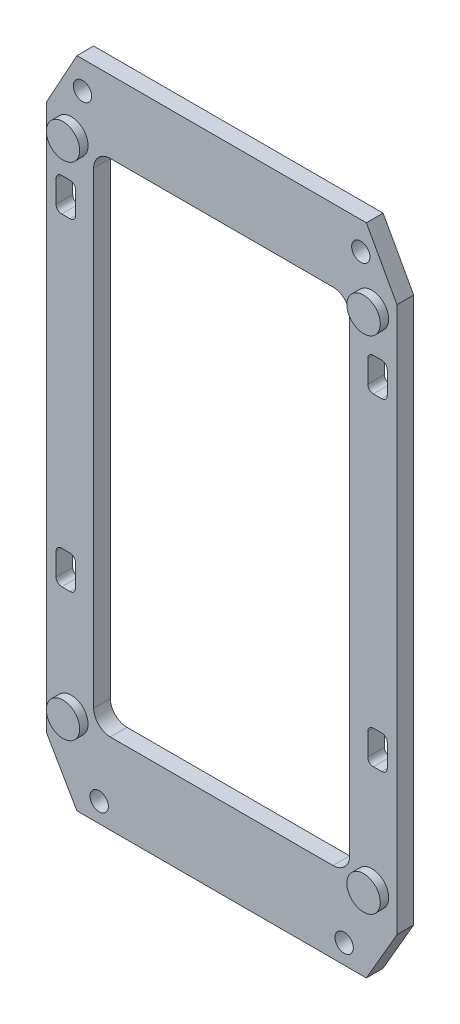
SolidWorks part; units mm, degrees
ref_plane "前视基准面" through (0, 0, 0) normal (0, 0, 1) x (1, 0, 0)
ref_plane "上视基准面" through (0, 0, 0) normal (0, 1, 0) x (1, 0, 0)
ref_plane "右视基准面" through (0, 0, 0) normal (1, 0, 0) x (0, 0, -1)
other "Configuration Table"
sketch "草图4" plane through (0, 0, 0) normal (0, 0, 1) x (1, 0, 0)
  line L12 (-26, -59.5) -> (26, -59.5)
  line L13 (26, -59.5) -> (31.5, -50)
  line L14 (31.5, -50) -> (31.5, 48)
  line L15 (31.5, 48) -> (26, 58)
  line L16 (26, 58) -> (-26, 58)
  line L17 (-26, 58) -> (-31.5, 48)
  line L18 (-31.5, 48) -> (-31.5, -50)
  line L19 (-31.5, -50) -> (-26, -59.5)
  line L20 (-20, -45) -> (20, -45)
  line L21 (23, -42) -> (23, 42)
  line L22 (20, 45) -> (-20, 45)
  line L23 (-23, 42) -> (-23, -42)
  arc A8 (20, -45) -> (23, -42) centre (20, -42) ccw
  arc A9 (23, 42) -> (20, 45) centre (20, 42) ccw
  arc A10 (-20, 45) -> (-23, 42) centre (-20, 42) ccw
  arc A11 (-23, -42) -> (-20, -45) centre (-20, -42) ccw
  circle A12 centre (-22, -56) radius 1.65
  circle A13 centre (-25, 53) radius 1.65
  circle A14 centre (22, -56) radius 1.65
  circle A15 centre (25, 53) radius 1.65
extrude "香橙派绝缘滑架_前端抽装" add sketch "草图4" along normal blind 3
sketch "草图5" plane through (0, 0, 0) normal (0, 0, 1) x (1, 0, 0)
  line L16 (-28.75, -26) -> (-27.25, -26)
  line L17 (-26.25, -25) -> (-26.25, -21)
  line L18 (-27.25, -20) -> (-28.75, -20)
  line L19 (-29.75, -21) -> (-29.75, -25)
  line L20 (-28.75, 32) -> (-27.25, 32)
  line L21 (-26.25, 33) -> (-26.25, 37)
  line L22 (-27.25, 38) -> (-28.75, 38)
  line L23 (-29.75, 37) -> (-29.75, 33)
  line L24 (27.25, -26) -> (28.75, -26)
  line L25 (29.75, -25) -> (29.75, -21)
  line L26 (28.75, -20) -> (27.25, -20)
  line L27 (26.25, -21) -> (26.25, -25)
  line L28 (27.25, 32) -> (28.75, 32)
  line L29 (29.75, 33) -> (29.75, 37)
  line L30 (28.75, 38) -> (27.25, 38)
  line L31 (26.25, 37) -> (26.25, 33)
  arc A20 (-27.25, -26) -> (-26.25, -25) centre (-27.25, -25) ccw
  arc A21 (-26.25, -21) -> (-27.25, -20) centre (-27.25, -21) ccw
  arc A22 (-28.75, -20) -> (-29.75, -21) centre (-28.75, -21) ccw
  arc A23 (-29.75, -25) -> (-28.75, -26) centre (-28.75, -25) ccw
  arc A24 (-27.25, 32) -> (-26.25, 33) centre (-27.25, 33) ccw
  arc A25 (-26.25, 37) -> (-27.25, 38) centre (-27.25, 37) ccw
  arc A26 (-28.75, 38) -> (-29.75, 37) centre (-28.75, 37) ccw
  arc A27 (-29.75, 33) -> (-28.75, 32) centre (-28.75, 33) ccw
  arc A28 (28.75, -26) -> (29.75, -25) centre (28.75, -25) ccw
  arc A29 (29.75, -21) -> (28.75, -20) centre (28.75, -21) ccw
  arc A30 (27.25, -20) -> (26.25, -21) centre (27.25, -21) ccw
  arc A31 (26.25, -25) -> (27.25, -26) centre (27.25, -25) ccw
  arc A32 (28.75, 32) -> (29.75, 33) centre (28.75, 33) ccw
  arc A33 (29.75, 37) -> (28.75, 38) centre (28.75, 37) ccw
  arc A34 (27.25, 38) -> (26.25, 37) centre (27.25, 37) ccw
  arc A35 (26.25, 33) -> (27.25, 32) centre (27.25, 33) ccw
extrude "绑带与脚架螺钉头避让" cut sketch "草图5" along normal blind 3
sketch "草图6" plane through (0, 0, 0) normal (0, 0, 1) x (1, 0, 0)
  circle A0 centre (-27, -45) radius 3
  circle A1 centre (-27, 45) radius 3
  circle A2 centre (27, -45) radius 3
  circle A3 centre (27, 45) radius 3
extrude "PCB下1p5mm绝缘支垫" add sketch "草图6" along normal blind 1.5 from offset 3
